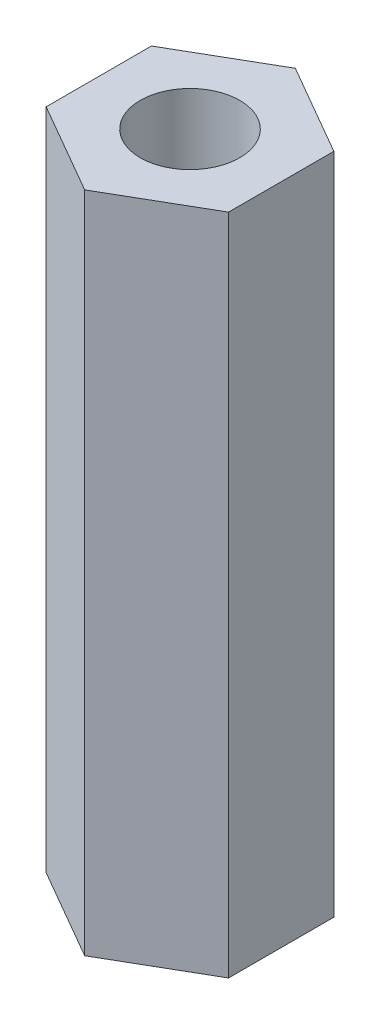
SolidWorks part; units mm, degrees
ref_plane "正面" through (0, 0, 0) normal (0, 0, 1) x (1, 0, 0)
ref_plane "平面" through (0, 0, 0) normal (0, 1, 0) x (1, 0, 0)
ref_plane "右側面" through (0, 0, 0) normal (1, 0, 0) x (0, 0, -1)
sketch "ｽｹｯﾁ1" plane through (0, 0, 0) normal (0, 1, 0) x (1, 0, 0)
  line L1 (0, -3.1754) -> (2.75, -1.5877)
  line L2 (2.75, -1.5877) -> (2.75, 1.5877)
  line L3 (2.75, 1.5877) -> (0, 3.1754)
  line L4 (0, 3.1754) -> (-2.75, 1.5877)
  line L5 (-2.75, 1.5877) -> (-2.75, -1.5877)
  line L6 (-2.75, -1.5877) -> (0, -3.1754)
  circle A0 centre (0, 0) radius 2.75 construction
  circle A1 centre (0, 0) radius 1.5
extrude "ﾎﾞｽ - 押し出し1" add sketch "ｽｹｯﾁ1" along normal blind 20
